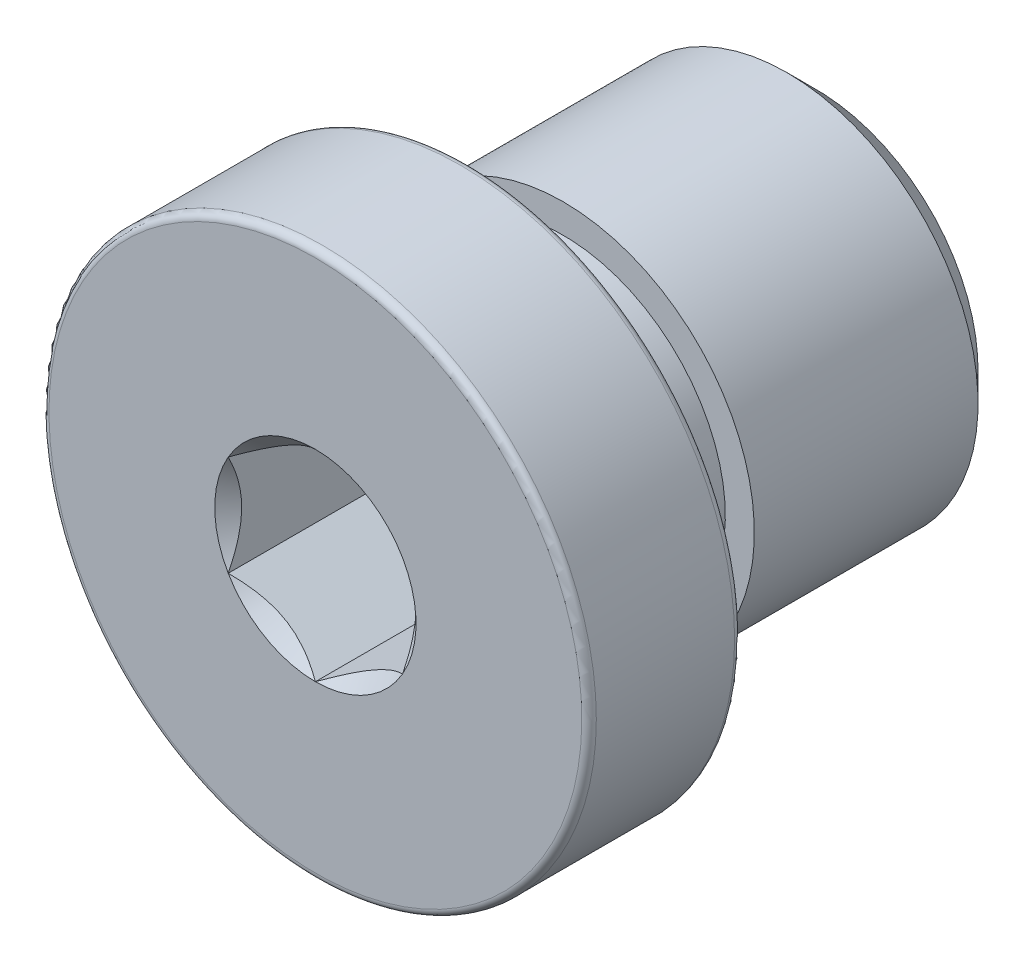
SolidWorks part; units mm, degrees
ref_plane "Front Plane" through (0, 0, 0) normal (0, 0, 1) x (1, 0, 0)
ref_plane "Top Plane" through (0, 0, 0) normal (0, 1, 0) x (1, 0, 0)
ref_plane "Right Plane" through (0, 0, 0) normal (1, 0, 0) x (0, 0, -1)
sketch "Sketch1" plane through (0, 0, 0) normal (1, 0, 0) x (0, 0, -1)
  line L0 (0, 0) -> (34.46, 0) construction
  line L1 (0, 0) -> (0, 9.42)
  line L2 (0, 9.42) -> (5.26, 9.42)
  line L3 (5.26, 9.42) -> (5.26, 7.745)
  line L4 (4.26, 5.58) -> (8.53, 5.58)
  line L5 (8.53, 5.58) -> (8.53, 6.5785)
  line L6 (8.53, 6.5785) -> (16.23, 6.5785)
  line L7 (16.23, 6.5785) -> (17.23, 5.5785)
  line L8 (17.23, 5.5785) -> (17.23, 0)
  line L9 (0, 0) -> (17.23, 0)
  line L10 (5.26, 7.745) -> (4.26, 7.745)
  line L11 (4.26, 7.745) -> (4.26, 5.58)
  dimension "D1" = 13.157
  dimension "D2" = 1
  dimension "D3" = 45
  dimension "D4" = 18.84
  dimension "D5" = 11.16
  dimension "D6" = 8.7
  dimension "D7" = 17.23
  dimension "D8" = 5.26
  dimension "D9" = 1.675
  dimension "D10" = 1
revolve "Revolve1" add sketch "Sketch1" angle 360 about L0
cosmetic thread "Cosmetic Thread1" parameters "D2"=19.015
sketch "Sketch2" plane through (0, 0, 0) normal (0, 0, 1) x (1, 0, 0)
  line L1 (0, 3.4641) -> (-3, 1.7321)
  line L2 (-3, 1.7321) -> (-3, -1.7321)
  line L3 (-3, -1.7321) -> (0, -3.4641)
  line L4 (0, -3.4641) -> (3, -1.7321)
  line L5 (3, -1.7321) -> (3, 1.7321)
  line L6 (3, 1.7321) -> (0, 3.4641)
  circle A0 centre (0, 0) radius 3 construction
  dimension "D1" = 6
extrude "Extrude1" cut sketch "Sketch2" against normal blind 8
fillet "Fillet1" radius 0.25 2 edges at (0, -9.42, 0) (0, -9.42, -5.26)
sketch "Sketch4" plane through (0, 0, -4.26) normal (0, 0, -1) x (-1, 0, 0)
  circle A0 centre (0, 0) radius 7.745 construction
  circle A1 centre (0, 0) radius 7.745
  circle A5 centre (0, 0) radius 6.545
  dimension "D1" = 1.2
extrude "Extrude3" add sketch "Sketch4" along normal blind 1.5
sketch "Sketch5" plane through (0, 0, 0) normal (1, 0, 0) x (0, 0, -1)
  line L0 (0, 3.4641) -> (0.8, 2.6641)
  line L1 (0.8, 2.6641) -> (0.8, 0)
  line L2 (0, 3.4641) -> (0, 0)
  line L3 (0, 0) -> (3.4649, 0) construction
  line L4 (0.8, 0) -> (0, 0)
  dimension "D1" = 0.8
  dimension "D2" = 45
revolve "Cut-Revolve1" cut sketch "Sketch5" angle 360 about L3
